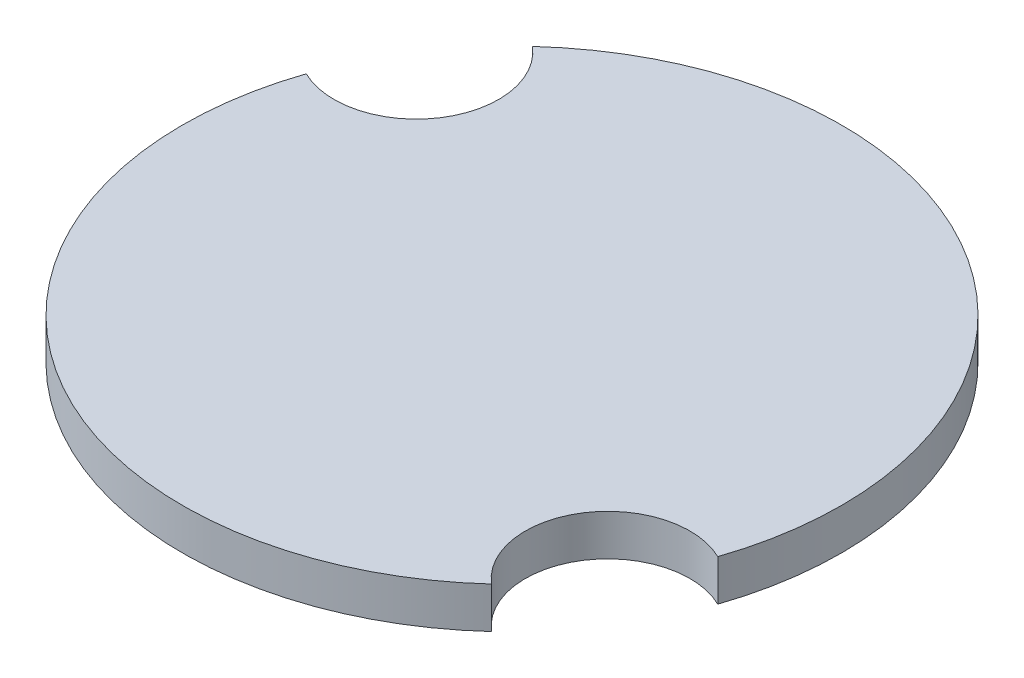
SolidWorks part; units mm, degrees
material "山毛榉"
ref_plane "前视基准面" through (0, 0, 0) normal (0, 0, 1) x (1, 0, 0)
ref_plane "上视基准面" through (0, 0, 0) normal (0, 1, 0) x (1, 0, 0)
ref_plane "右视基准面" through (0, 0, 0) normal (1, 0, 0) x (0, 0, -1)
sketch "草图1" plane through (0, 0, 0) normal (0, 1, 0) x (1, 0, 0)
  circle A0 centre (27.5149, -26.4159) radius 40
extrude "凸台-拉伸1" add sketch "草图1" along normal blind 5
sketch3d "3D草图1"
  circle A0 centre (-5.9718, 5, 4.5382) radius 10
  circle A2 centre (27.5149, 5, 26.4159) radius 40 construction
  circle A3 centre (61.0017, 5, 48.2937) radius 10
  point P2 (-5.9718, -5, 4.5382)
  point P5 (27.5149, 45, 26.4159)
  point P8 (61.0017, -5, 48.2937)
extrude "切除-拉伸1" cut sketch "3D草图1" along a picked direction on the side of the normal blind 16
